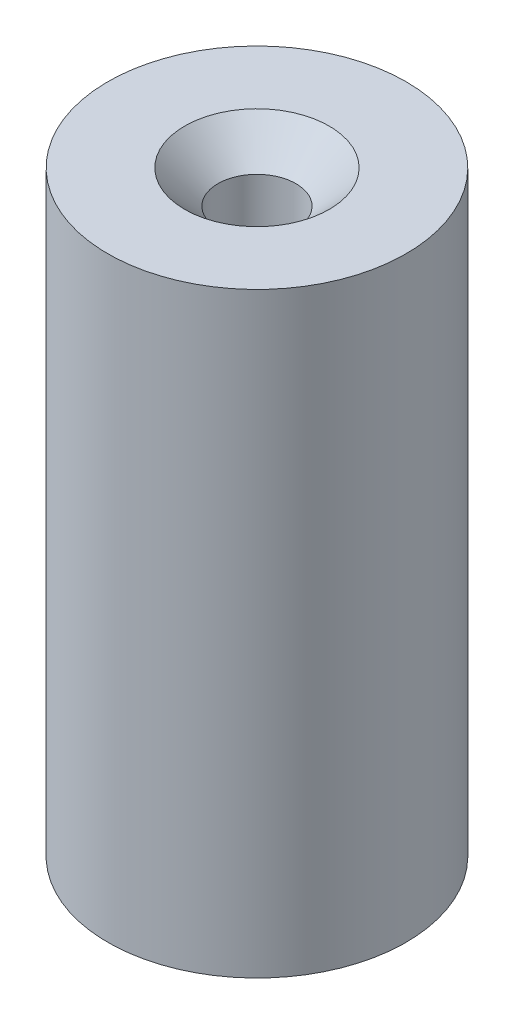
SolidWorks part; units mm, degrees
ref_plane "Спереди" through (0, 0, 0) normal (0, 0, 1) x (1, 0, 0)
ref_plane "Сверху" through (0, 0, 0) normal (0, 1, 0) x (1, 0, 0)
ref_plane "Справа" through (0, 0, 0) normal (1, 0, 0) x (0, 0, -1)
sketch "Эскиз1" plane through (0, 0, 0) normal (0, 1, 0) x (1, 0, 0)
  circle A0 centre (0, 0) radius 6.5
  dimension "D1" = 13
extrude "Бобышка-Вытянуть1" add sketch "Эскиз1" along normal blind 26
sketch "Эскиз2" plane through (0, 0, 0) normal (0, -1, 0) x (1, 0, 0)
  circle A0 centre (0, 0) radius 2.85
  dimension "D1" = 5.7
extrude "Вырез-Вытянуть1" cut sketch "Эскиз2" against normal blind 3.5
hole_wizard "Зенковка для  винта с плоской головкой M32" positions "Эскиз4" profile "Эскиз3" countersink size "M3" standard "Ansi Metric" end condition through all
sketch "Эскиз4" plane through (0, 26, 0) normal (0, 1, 0) x (1, 0, 0)
  point P0 (0, 0)
sketch "Эскиз3" plane through (0, 26, 0) normal (1, 0, 0) x (0, 0, 1)
  line L0 (0, 0) -> (0, 26)
  line L1 (0, 26) -> (1.7, 26)
  line L2 (1.7, 26) -> (1.7, 1.45)
  line L3 (1.7, 1.45) -> (3.15, 0)
  line L5 (3.15, 0) -> (0, 0)
  line L6 (-1.7, 1.45) -> (-3.15, 0) construction
  line L11 (0, -6.35) -> (0, 107.95) construction
  dimension "Диаметр сквозного отверстия" = 3.4
  dimension "Глубина сквозного отверстия" = 26
  dimension "Диаметр передней зенковки" = 6.3
  dimension "Угол передней зенковки" = 90
